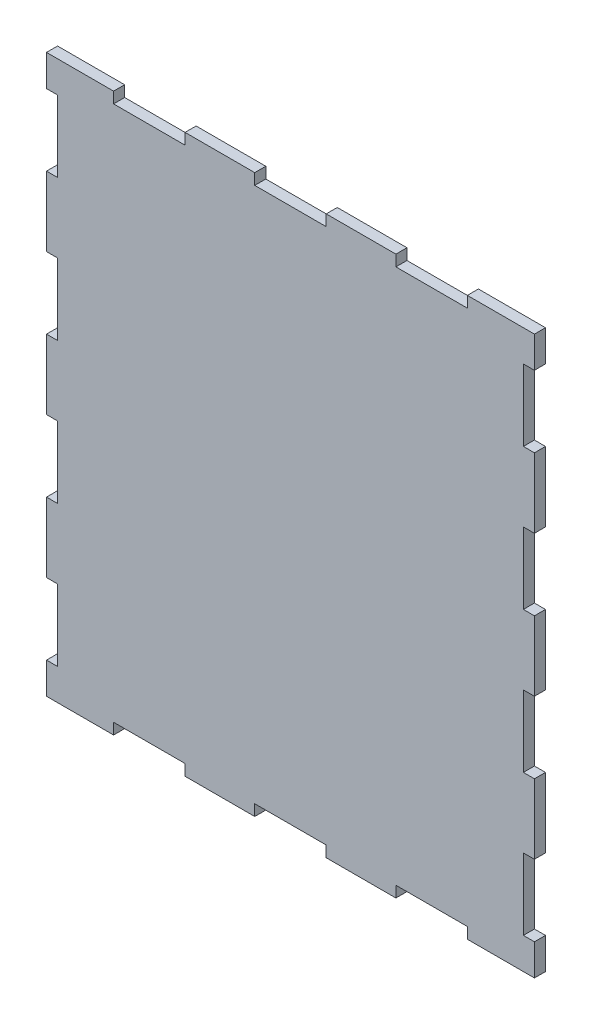
SolidWorks part; units mm, degrees
ref_plane "Front Plane" through (0, 0, 0) normal (0, 0, 1) x (1, 0, 0)
ref_plane "Top Plane" through (0, 0, 0) normal (0, 1, 0) x (1, 0, 0)
ref_plane "Right Plane" through (0, 0, 0) normal (1, 0, 0) x (0, 0, -1)
sketch "Sketch1" plane through (0, 0, 0) normal (0, 0, 1) x (1, 0, 0)
  line L1 (-64.0181, 0) -> (75.9819, 0)
  line L2 (-64.0181, 0) -> (-64.0181, 160)
  line L3 (-64.0181, 160) -> (75.9819, 160)
  line L4 (75.9819, 0) -> (75.9819, 160)
extrude "Boss-Extrude1" add sketch "Sketch1" along normal blind 3.175
sketch "Sketch2" plane through (0, 0, 3.175) normal (0, 0, 1) x (1, 0, 0)
  line L0 (-64.0181, 29.5) -> (-60.8431, 29.5) construction
  line L1 (-60.8431, 29.5) -> (-60.8431, 9) construction
  line L2 (-60.8431, 9) -> (-64.0181, 9) construction
  line L3 (-64.0181, 9) -> (-64.0181, 29.5) construction
  line L4 (-64.0181, 70) -> (-60.8431, 70) construction
  line L5 (-60.8431, 70) -> (-60.8431, 49.5) construction
  line L6 (-60.8431, 49.5) -> (-64.0181, 49.5) construction
  line L7 (-64.0181, 49.5) -> (-64.0181, 70) construction
  line L8 (-64.0181, 110.5) -> (-60.8431, 110.5) construction
  line L9 (-60.8431, 110.5) -> (-60.8431, 90) construction
  line L10 (-60.8431, 90) -> (-64.0181, 90) construction
  line L11 (-64.0181, 90) -> (-64.0181, 110.5) construction
  line L12 (-64.0181, 151) -> (-60.8431, 151) construction
  line L13 (-60.8431, 151) -> (-60.8431, 130.5) construction
  line L14 (-60.8431, 130.5) -> (-64.0181, 130.5) construction
  line L15 (-64.0181, 130.5) -> (-64.0181, 151) construction
  line L16 (-24.2681, 160) -> (-24.2681, 156.825) construction
  line L17 (-24.2681, 156.825) -> (-44.7681, 156.825) construction
  line L18 (-44.7681, 156.825) -> (-44.7681, 160) construction
  line L19 (-44.7681, 160) -> (-24.2681, 160) construction
  line L20 (16.2319, 160) -> (16.2319, 156.825) construction
  line L21 (16.2319, 156.825) -> (-4.2681, 156.825) construction
  line L22 (-4.2681, 156.825) -> (-4.2681, 160) construction
  line L23 (-4.2681, 160) -> (16.2319, 160) construction
  line L24 (56.7319, 160) -> (56.7319, 156.825) construction
  line L25 (56.7319, 156.825) -> (36.2319, 156.825) construction
  line L26 (36.2319, 156.825) -> (36.2319, 160) construction
  line L27 (36.2319, 160) -> (56.7319, 160) construction
  line L28 (72.8069, 151) -> (75.9819, 151) construction
  line L29 (75.9819, 151) -> (75.9819, 130.5) construction
  line L30 (75.9819, 130.5) -> (72.8069, 130.5) construction
  line L31 (72.8069, 130.5) -> (72.8069, 151) construction
  line L32 (72.8069, 110.5) -> (75.9819, 110.5) construction
  line L33 (75.9819, 110.5) -> (75.9819, 90) construction
  line L34 (75.9819, 90) -> (72.8069, 90) construction
  line L35 (72.8069, 90) -> (72.8069, 110.5) construction
  line L36 (72.8069, 70) -> (75.9819, 70) construction
  line L37 (75.9819, 70) -> (75.9819, 49.5) construction
  line L38 (75.9819, 49.5) -> (72.8069, 49.5) construction
  line L39 (72.8069, 49.5) -> (72.8069, 70) construction
  line L40 (72.8069, 29.5) -> (75.9819, 29.5) construction
  line L41 (75.9819, 29.5) -> (75.9819, 9) construction
  line L42 (75.9819, 9) -> (72.8069, 9) construction
  line L43 (72.8069, 9) -> (72.8069, 29.5) construction
  line L44 (36.2319, 0) -> (36.2319, 3.175) construction
  line L45 (36.2319, 3.175) -> (56.7319, 3.175) construction
  line L46 (56.7319, 3.175) -> (56.7319, 0) construction
  line L47 (56.7319, 0) -> (36.2319, 0) construction
  line L48 (-4.2681, 0) -> (-4.2681, 3.175) construction
  line L49 (-4.2681, 3.175) -> (16.2319, 3.175) construction
  line L50 (16.2319, 3.175) -> (16.2319, 0) construction
  line L51 (16.2319, 0) -> (-4.2681, 0) construction
  line L52 (-44.7681, 0) -> (-44.7681, 3.175) construction
  line L53 (-44.7681, 3.175) -> (-24.2681, 3.175) construction
  line L54 (-24.2681, 3.175) -> (-24.2681, 0) construction
  line L55 (-24.2681, 0) -> (-44.7681, 0) construction
  line L56 (-64.0181, 29.5) -> (-60.8431, 29.5)
  line L57 (-60.8431, 29.5) -> (-60.8431, 9)
  line L58 (-60.8431, 9) -> (-64.0181, 9)
  line L59 (-64.0181, 9) -> (-64.0181, 29.5)
  line L60 (-64.0181, 70) -> (-60.8431, 70)
  line L61 (-60.8431, 70) -> (-60.8431, 49.5)
  line L62 (-60.8431, 49.5) -> (-64.0181, 49.5)
  line L63 (-64.0181, 49.5) -> (-64.0181, 70)
  line L64 (-64.0181, 110.5) -> (-60.8431, 110.5)
  line L65 (-60.8431, 110.5) -> (-60.8431, 90)
  line L66 (-60.8431, 90) -> (-64.0181, 90)
  line L67 (-64.0181, 90) -> (-64.0181, 110.5)
  line L68 (-64.0181, 151) -> (-60.8431, 151)
  line L69 (-60.8431, 151) -> (-60.8431, 130.5)
  line L70 (-60.8431, 130.5) -> (-64.0181, 130.5)
  line L71 (-64.0181, 130.5) -> (-64.0181, 151)
  line L72 (-24.2681, 160) -> (-24.2681, 156.825)
  line L73 (-24.2681, 156.825) -> (-44.7681, 156.825)
  line L74 (-44.7681, 156.825) -> (-44.7681, 160)
  line L75 (-44.7681, 160) -> (-24.2681, 160)
  line L76 (16.2319, 160) -> (16.2319, 156.825)
  line L77 (16.2319, 156.825) -> (-4.2681, 156.825)
  line L78 (-4.2681, 156.825) -> (-4.2681, 160)
  line L79 (-4.2681, 160) -> (16.2319, 160)
  line L80 (56.7319, 160) -> (56.7319, 156.825)
  line L81 (56.7319, 156.825) -> (36.2319, 156.825)
  line L82 (36.2319, 156.825) -> (36.2319, 160)
  line L83 (36.2319, 160) -> (56.7319, 160)
  line L84 (72.8069, 151) -> (75.9819, 151)
  line L85 (75.9819, 151) -> (75.9819, 130.5)
  line L86 (75.9819, 130.5) -> (72.8069, 130.5)
  line L87 (72.8069, 130.5) -> (72.8069, 151)
  line L88 (72.8069, 110.5) -> (75.9819, 110.5)
  line L89 (75.9819, 110.5) -> (75.9819, 90)
  line L90 (75.9819, 90) -> (72.8069, 90)
  line L91 (72.8069, 90) -> (72.8069, 110.5)
  line L92 (72.8069, 70) -> (75.9819, 70)
  line L93 (75.9819, 70) -> (75.9819, 49.5)
  line L94 (75.9819, 49.5) -> (72.8069, 49.5)
  line L95 (72.8069, 49.5) -> (72.8069, 70)
  line L96 (72.8069, 29.5) -> (75.9819, 29.5)
  line L97 (75.9819, 29.5) -> (75.9819, 9)
  line L98 (75.9819, 9) -> (72.8069, 9)
  line L99 (72.8069, 9) -> (72.8069, 29.5)
  line L100 (36.2319, 0) -> (36.2319, 3.175)
  line L101 (36.2319, 3.175) -> (56.7319, 3.175)
  line L102 (56.7319, 3.175) -> (56.7319, 0)
  line L103 (56.7319, 0) -> (36.2319, 0)
  line L104 (-4.2681, 0) -> (-4.2681, 3.175)
  line L105 (-4.2681, 3.175) -> (16.2319, 3.175)
  line L106 (16.2319, 3.175) -> (16.2319, 0)
  line L107 (16.2319, 0) -> (-4.2681, 0)
  line L108 (-44.7681, 0) -> (-44.7681, 3.175)
  line L109 (-44.7681, 3.175) -> (-24.2681, 3.175)
  line L110 (-24.2681, 3.175) -> (-24.2681, 0)
  line L111 (-24.2681, 0) -> (-44.7681, 0)
extrude "Cut-Extrude1" cut sketch "Sketch2" against normal up to surface (3.175 mm away) up to face at (5.9819, 80, 0)
